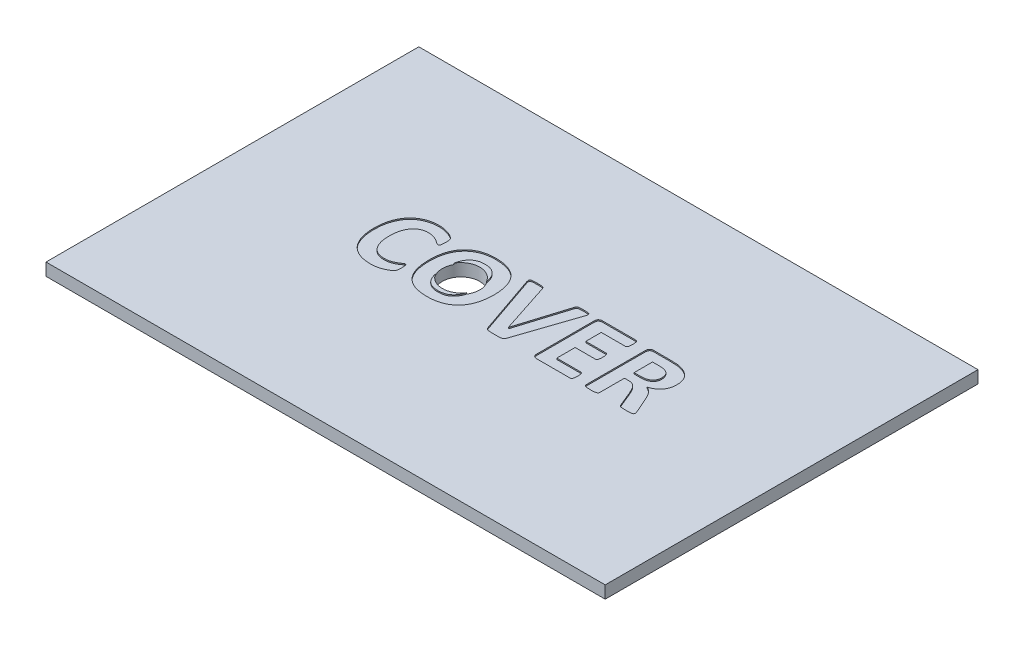
SolidWorks part; units mm, degrees
material "ABS PC"
ref_plane "Front Plane" through (0, 0, 0) normal (0, 0, 1) x (1, 0, 0)
ref_plane "Top Plane" through (0, 0, 0) normal (0, 1, 0) x (1, 0, 0)
ref_plane "Right Plane" through (0, 0, 0) normal (1, 0, 0) x (0, 0, -1)
sketch "Sketch1" plane through (0, 0, 0) normal (0, 1, 0) x (1, 0, 0)
  line L1 (-225, 150) -> (225, 150)
  line L2 (-225, 150) -> (-225, -150)
  line L3 (-225, -150) -> (225, -150)
  line L4 (225, 150) -> (225, -150)
  line L5 (-225, 150) -> (225, -150) construction
  line L6 (-225, -150) -> (225, 150) construction
  point P0 (0, 0)
  dimension "D1" = 450
  dimension "D2" = 300
extrude "Boss-Extrude1" add sketch "Sketch1" along normal blind 10
sketch "Sketch2" plane through (0, 10, 0) normal (0, 1, 0) x (1, 0, 0)
  line L0 (-225, -20) -> (225, -20) construction
  line L1 (-225, 150) -> (-225, -150) construction
  line L2 (225, -150) -> (225, 150) construction
  line L3 (-225, -150) -> (225, -150) construction
  text T0 "COVER" font "Calibri" height in points 200
  dimension "D1" = 130
extrude "Cut-Extrude1" cut sketch "Sketch2" against normal blind 1
sketch "Sketch3" plane through (0, 10, 0) normal (0, 1, 0) x (1, 0, 0)
  line L0 (-225, -150) -> (225, -150) construction
  line L1 (-225, 150) -> (-225, -150) construction
  circle A0 centre (-47, 6) radius 15
  point P2 (0, 0)
  dimension "D1" = 30
  dimension "D3" = 178
  dimension "D2" = 156
extrude "Cut-Extrude2" cut sketch "Sketch3" against normal through all
